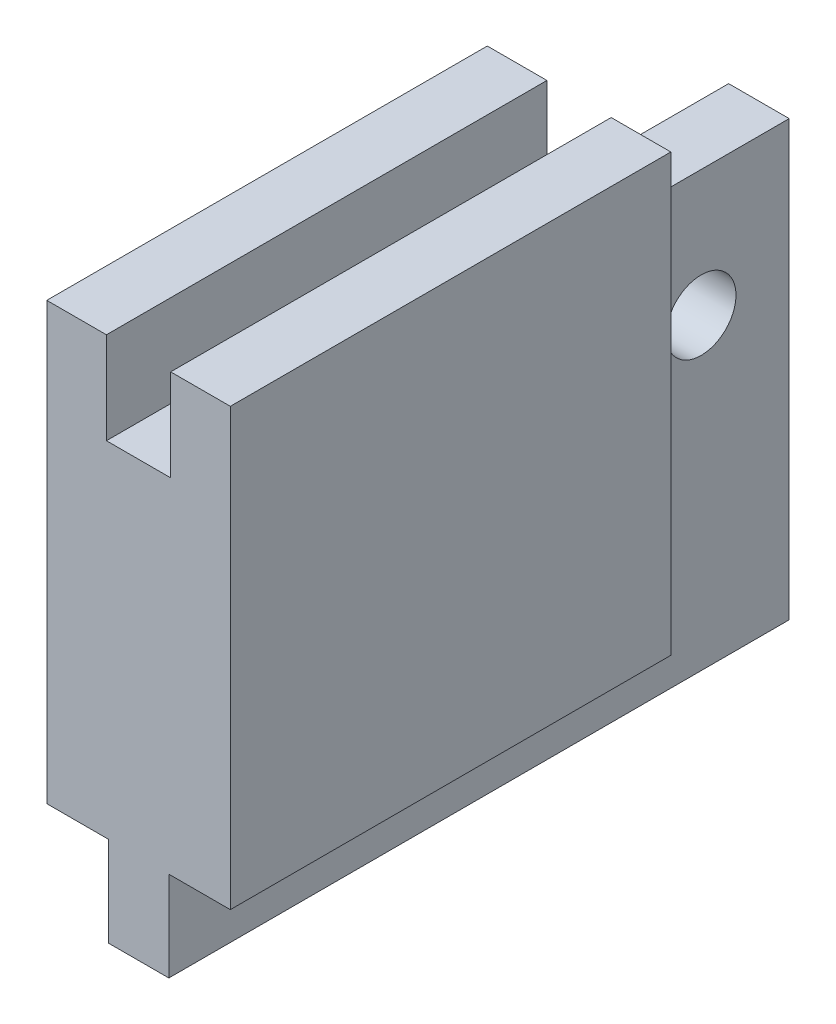
SolidWorks part; units mm, degrees
ref_plane "Front Plane" through (0, 0, 0) normal (1, 0, 0) x (0, 1, 0)
ref_plane "Top Plane" through (0, 0, 0) normal (0, 0, 1) x (0, 1, 0)
ref_plane "Right Plane" through (0, 0, 0) normal (0, 1, 0) x (-1, 0, 0)
sketch "Sketch1" plane through (0, 0, 0) normal (1, 0, 0) x (0, 1, 0)
  line L1 (0, 0) -> (23.75, 0)
  line L2 (0, 0) -> (0, 24)
  line L3 (0, 24) -> (23.75, 24)
  line L4 (23.75, 0) -> (23.75, 24)
  dimension "D1" = 23.75
  dimension "D2" = 24
extrude "Boss-Extrude1" add sketch "Sketch1" against normal blind 10
sketch "Sketch2" plane through (0, 0, 0) normal (0, -1, 0) x (1, 0, 0)
  line L1 (-10, 0) -> (-6.65, 0)
  line L2 (-10, 0) -> (-10, -9.8)
  line L3 (-10, -9.8) -> (-6.65, -9.8)
  line L4 (-6.65, 0) -> (-6.65, -9.8)
  line L5 (0, 0) -> (-3.35, 0)
  line L6 (0, 0) -> (0, -9.8)
  line L7 (0, -9.8) -> (-3.35, -9.8)
  line L8 (-3.35, 0) -> (-3.35, -9.8)
  line L9 (-6.65, -9.8) -> (-3.35, -9.8)
  line L10 (-6.65, -9.8) -> (-6.65, 0)
  line L11 (-6.65, 0) -> (-3.35, 0)
  line L12 (-3.35, -9.8) -> (-3.35, 0)
  line M12 (-10, 0) -> (0, 0)
  dimension "D1" = 9.8
  dimension "D2" = 3.35
  dimension "D3" = 3.35
extrude "Boss-Extrude2" add sketch "Sketch2" against normal through all contours L4 L9 L8 M12
sketch "Sketch3" plane through (0, 0, 0) normal (0, -1, 0) x (1, 0, 0)
  line L0 (-3.35, 20.65) -> (-3.35, 3.35)
  line L1 (0, 24) -> (-10, 24)
  line L2 (0, 24) -> (0, 0)
  line L3 (0, 0) -> (-10, 0)
  line L4 (-10, 24) -> (-10, 0)
  line L5 (-3.35, 3.35) -> (-6.65, 3.35)
  line L6 (-6.65, 20.65) -> (-6.65, 3.35)
  line L7 (-3.35, 20.65) -> (-6.65, 20.65)
  line L9 (-6.65, 20.65) -> (-3.35, 20.65)
  line L10 (-6.65, 20.65) -> (-6.65, 24)
  line L11 (-6.65, 24) -> (-3.35, 24)
  line L12 (-3.35, 20.65) -> (-3.35, 24)
  line L13 (-6.65, 3.35) -> (-3.35, 3.35)
  line L14 (-6.65, 3.35) -> (-6.65, -9.8)
  line L15 (-6.65, -9.8) -> (-3.35, -9.8)
  line L16 (-3.35, 3.35) -> (-3.35, -9.8)
  dimension "D1" = 3.35
extrude "Boss-Extrude3" add sketch "Sketch3" along normal blind 4.9 contours L0 L7 L6 L5 | L10 L9 L12 L11 | L14 L13 L16 L15
sketch "Sketch4" plane through (-6.65, 0, 0) normal (-1, 0, 0) x (0, -1, 0)
  line L0 (0, 0) -> (-23.75, 0) construction
  line L1 (-11.875, 0) -> (-23.75, 0)
  line L2 (-11.875, 0) -> (-11.875, -5)
  line L3 (-11.875, -5) -> (-23.75, -5)
  line L4 (-23.75, 0) -> (-23.75, -5)
  circle A0 centre (-11.875, -5) radius 1.9
  dimension "D2" = 3.8
  dimension "D1" = 5
extrude "Cut-Extrude1" cut sketch "Sketch4" against normal up to next contours A0
sketch "Sketch5" plane through (0, 23.75, 0) normal (0, 1, 0) x (-1, 0, 0)
  line L0 (3.25, 20.75) -> (3.25, 3.25)
  line L1 (0, 24) -> (10, 24)
  line L2 (0, 24) -> (0, 0)
  line L3 (0, 0) -> (10, 0)
  line L4 (10, 24) -> (10, 0)
  line L5 (3.25, 3.25) -> (6.75, 3.25)
  line L6 (6.75, 20.75) -> (6.75, 3.25)
  line L7 (3.25, 20.75) -> (6.75, 20.75)
  line L9 (3.25, 20.75) -> (6.75, 20.75)
  line L10 (3.25, 20.75) -> (3.25, 24)
  line L11 (3.25, 24) -> (6.75, 24)
  line L12 (6.75, 20.75) -> (6.75, 24)
  line L13 (3.25, 3.25) -> (6.75, 3.25)
  line L14 (3.25, 3.25) -> (3.25, -9.8)
  line L15 (3.25, -9.8) -> (6.75, -9.8)
  line L16 (6.75, 3.25) -> (6.75, -9.8)
  point P15 (6.2824, -9.8)
  point P16 (6.5259, 3.25)
  dimension "D1" = 3.25
extrude "Cut-Extrude2" cut sketch "Sketch5" against normal blind 5 contours L10 L9 L12 L11 | L0 L5 L6 L7 | L14 L13 L16 L15
equation "\"whitekey_cutout_length\"= 101.5"
equation "\"key_mount_recess_length\"=50"
equation "\"key_mount_recess_height\"=12.5"
equation "\"key_mount_recess_depth\"=1.5"
equation "\"wall_thickness\"=10"
equation "\"guide_brace_height\"=20"
equation "\"guide_brace_thickness\"=2"
equation "\"dowel_recess_depth\"=10"
equation "\"dowel_recess_offset\"=3.25"
equation "\"base_mount_height\"=40"
equation "\"base_rear_length\"=80"
equation "\"base_front_length\"=111.5"
equation "\"screw_hole_wall_offset\"=7.25"
equation "\"screw_hole_edge_inset\"=\"dowel_recess_depth\"/2"
equation "\"screw_hole_diameter\"=3.8"
equation "\"screw_head_hole_diameter\"=6.7"
equation "\"screw_nut_hole_side_len\"=3.5"
equation "\"screw_shaft_diameter\"=3.5"
equation "\"switch_board_width\"=30"
equation "\"switch_board_wall_offset\"=11.5"
equation "\"heatset_insert_hole_diameter\"=4.8"
equation "\"heatset_insert_hole_depth\"=3.8"
equation "\"D1@Boss-Extrude1\"=\"wall_thickness\""
equation "\"D2@Sketch2\"=\"dowel_recess_offset\"+\"dowel_insert_tolerance\""
equation "\"D3@Sketch2\"=\"dowel_recess_offset\"+\"dowel_insert_tolerance\""
equation "\"D1@Boss-Extrude3\"=\"front_rear_panel_recess_depth\"-\"dowel_insert_tolerance\""
equation "\"D1@Sketch3\"=\"dowel_recess_offset\"+\"dowel_insert_tolerance\""
equation "\"D1@Sketch2\"=\"dowel_recess_depth\"-\"dowel_insert_tolerance\"*2"
equation "\"D1@Sketch4\"=\"screw_hole_edge_inset\""
equation "\"D2@Sketch4\"=\"screw_hole_diameter\""
equation "\"D1@Sketch5\"=\"dowel_recess_offset\""
equation "\"D1@Cut-Extrude2\"=\"front_rear_panel_recess_depth\""
equation "\"screw_nut_recess_offset\"=0.35"
equation "\"screw_head_and_nut_recess_depth\"=2.5"
equation "\"front_rear_panel_width\"=23.75"
equation "\"rod_length_adj\"=0.5"
equation "\"rod_insert_length\"=2.8"
equation "\"D1@Sketch1\"=\"front_rear_panel_width\""
equation "\"switch_board_thickness\"=1.6"
equation "\"front_panel_height\"=24"
equation "\"rod_diameter\"=5"
equation "\"rod_head_diameter\"=8"
equation "\"switch_black_key_mount_height\"=8"
equation "\"switch_white_key_mount_height\"=3"
equation "\"D2@Sketch1\"=\"front_panel_height\""
equation "\"dowel_insert_tolerance\"=0.1"
equation "\"front_rear_panel_recess_depth\"=5"
